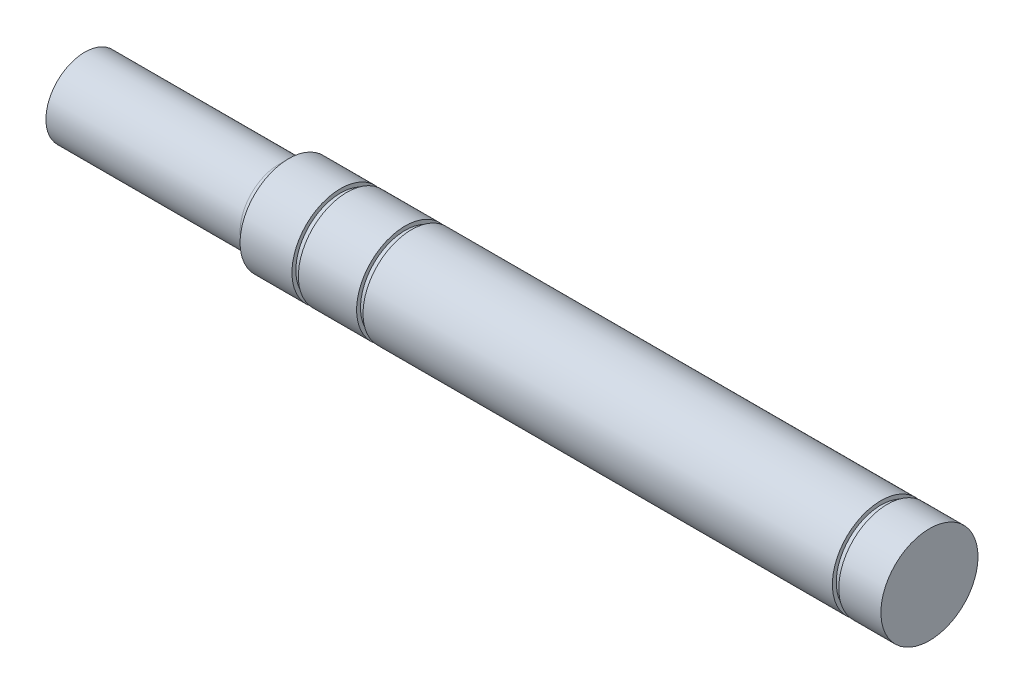
SolidWorks part; units mm, degrees
material "AISI 1020"
ref_plane "Front Plane" through (0, 0, 0) normal (0, 0, 1) x (1, 0, 0)
ref_plane "Top Plane" through (0, 0, 0) normal (0, 1, 0) x (1, 0, 0)
ref_plane "Right Plane" through (0, 0, 0) normal (1, 0, 0) x (0, 0, -1)
sketch "Sketch1" plane through (0, 0, 0) normal (0, 0, 1) x (-1, 0, 0)
  line L0 (93.2457, 287.7549) -> (93.2457, 287.3549)
  line L1 (93.2457, 287.3549) -> (93.9057, 287.3549)
  line L2 (93.9057, 287.3549) -> (93.9057, 287.7549)
  line L3 (93.9057, 287.7549) -> (99.2457, 287.7549)
  line L4 (37.5857, 287.7549) -> (37.5857, 287.3549)
  line L5 (37.5857, 287.3549) -> (38.2457, 287.3549)
  line L6 (38.2457, 287.3549) -> (38.2457, 287.7549)
  line L8 (87.2457, 287.7549) -> (87.2457, 287.3549)
  line L9 (87.2457, 287.3549) -> (86.5857, 287.3549)
  line L10 (86.5857, 287.3549) -> (86.5857, 287.7549)
  line L11 (87.2457, 287.7549) -> (93.2457, 287.7549)
  line L19 (120.2457, 286.7549) -> (120.2457, 282.7549)
  line L20 (37.5857, 287.7549) -> (33.2457, 287.7549)
  line L21 (33.2457, 287.7549) -> (33.2457, 282.7549)
  line L22 (33.2457, 282.7549) -> (120.2457, 282.7549) construction
  line L23 (120.2457, 286.7549) -> (100.2457, 286.7549)
  line L28 (38.2457, 287.7549) -> (86.5857, 287.7549)
  arc A0 (100.2457, 286.7549) -> (99.2457, 287.7549) centre (100.2457, 287.7549) cw
  point P3 (93.9057, 287.7549)
  point P14 (93.2457, 287.7549)
  dimension "D1" = 0.66
  dimension "D2" = 5
  dimension "D4" = 4
  dimension "D6" = 5
  dimension "D7" = 60
  dimension "D8" = 0.66
  dimension "D9" = 87
  dimension "D11" = 20
  dimension "D12" = 0.4
  dimension "D13" = 0.66
  dimension "D14" = 0.4
  dimension "D15" = 5
  dimension "D16" = 6
  dimension "D17" = 21
revolve "Revolve1" add sketch "Sketch1" angle 360 about L22
sketch "Sketch3" plane through (-120.2457, 0, 0) normal (-1, 0, 0) x (0, 0, 1)
  circle A0 centre (0, -282.7549) radius 4
curve "Helix/Spiral1" pitch 1.25 height 10 turns 8
sketch "Sketch4" plane through (-120.2457, 0, 0) normal (-1, 0, 0) x (0, 0, 1)
  line L0 (0, -282.7549) -> (3.9894, -282.7549)
sketch "Sketch5" plane through (-120.2457, 0, 0) normal (-1, 0, 0) x (0, 0, 1)
  line L0 (0, -282.7549) -> (0, -287.7549)
  circle A0 centre (0, -282.7549) radius 5 construction
sketch "Sketch6" plane through (-120.2457, 0, 0) normal (-1, 0, 0) x (0, 0, 1)
  line L0 (0, -282.7549) -> (0, -286.7549)
  circle A0 centre (0, -282.7549) radius 4 construction
